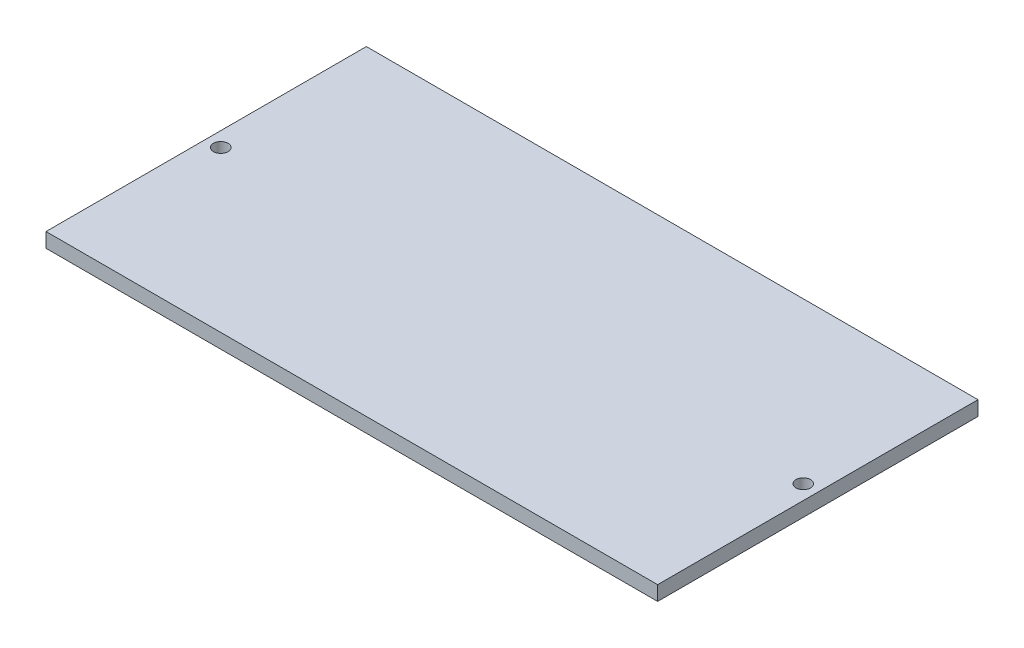
SolidWorks part; units mm, degrees
ref_plane "Front Plane" through (0, 0, 0) normal (0, 0, 1) x (1, 0, 0)
ref_plane "Top Plane" through (0, 0, 0) normal (0, 1, 0) x (1, 0, 0)
ref_plane "Right Plane" through (0, 0, 0) normal (1, 0, 0) x (0, 0, -1)
sketch "Sketch1" plane through (0, 0, 0) normal (0, 1, 0) x (1, 0, 0)
  line L1 (-42, 22) -> (42, 22)
  line L2 (-42, 22) -> (-42, -22)
  line L3 (-42, -22) -> (42, -22)
  line L4 (42, 22) -> (42, -22)
  line L5 (-42, 22) -> (42, -22) construction
  line L6 (-42, -22) -> (42, 22) construction
  point P0 (0, 0)
  dimension "D1" = 84
  dimension "D2" = 44
extrude "Boss-Extrude1" add sketch "Sketch1" along normal blind 2
sketch "Sketch2" plane through (0, 2, 0) normal (0, 1, 0) x (1, 0, 0)
  line L0 (-42, 22) -> (-42, -22) construction
  line L1 (42, 22) -> (-42, 22) construction
  line L2 (42, -22) -> (42, 22) construction
  circle A0 centre (-40, 0) radius 1
  circle A1 centre (40, 0) radius 1
  dimension "D1" = 2
  dimension "D5" = 2
  dimension "D6" = 2
  dimension "D2" = 22
  dimension "D3" = 22
  dimension "D4" = 2
extrude "Cut-Extrude1" cut sketch "Sketch2" against normal blind 10
